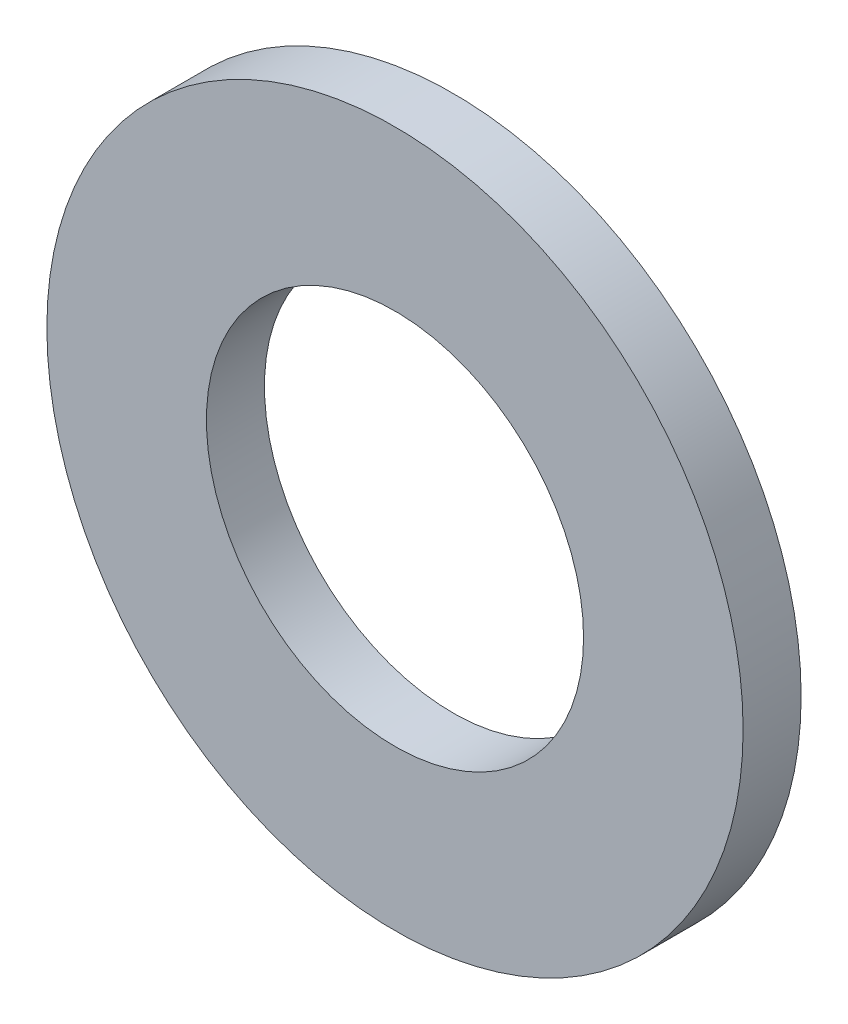
SolidWorks part; units mm, degrees
ref_plane "Front Plane" through (0, 0, 0) normal (0, 0, 1) x (1, 0, 0)
ref_plane "Top Plane" through (0, 0, 0) normal (0, 1, 0) x (1, 0, 0)
ref_plane "Right Plane" through (0, 0, 0) normal (1, 0, 0) x (0, 0, -1)
sketch "Sketch1" plane through (0, 0, 0) normal (0, 0, 1) x (1, 0, 0)
  circle A0 centre (0, 0) radius 6
  circle A1 centre (0, 0) radius 3.25
  dimension "D1" = 12
  dimension "D2" = 6.5
extrude "Boss-Extrude1" add sketch "Sketch1" along normal blind 1
